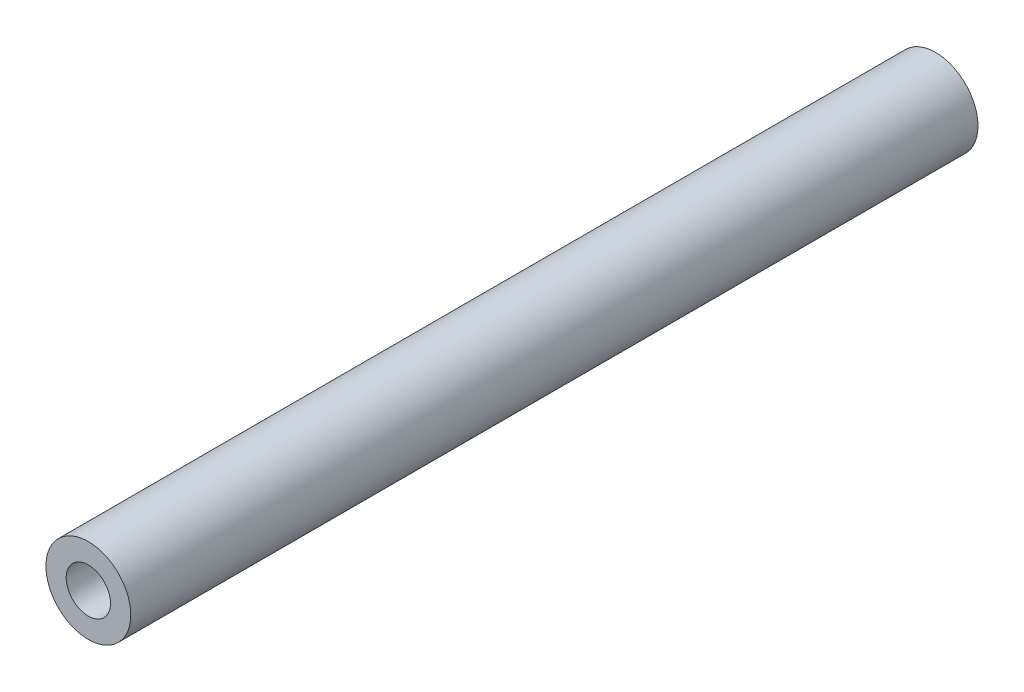
SolidWorks part; units mm, degrees
material "6061-T6 (SS)"
ref_plane "Front Plane" through (0, 0, 0) normal (0, 0, 1) x (1, 0, 0)
ref_plane "Top Plane" through (0, 0, 0) normal (0, 1, 0) x (1, 0, 0)
ref_plane "Right Plane" through (0, 0, 0) normal (1, 0, 0) x (0, 0, -1)
sketch "Sketch1" plane through (0, 0, 0) normal (0, 0, 1) x (1, 0, 0)
  circle A0 centre (0, 0) radius 4.7625
  circle A1 centre (0, 0) radius 2.4892
  dimension "D1" = 9.525
  dimension "D2" = 4.9784
extrude "Boss-Extrude1" add sketch "Sketch1" against normal blind 95.123
